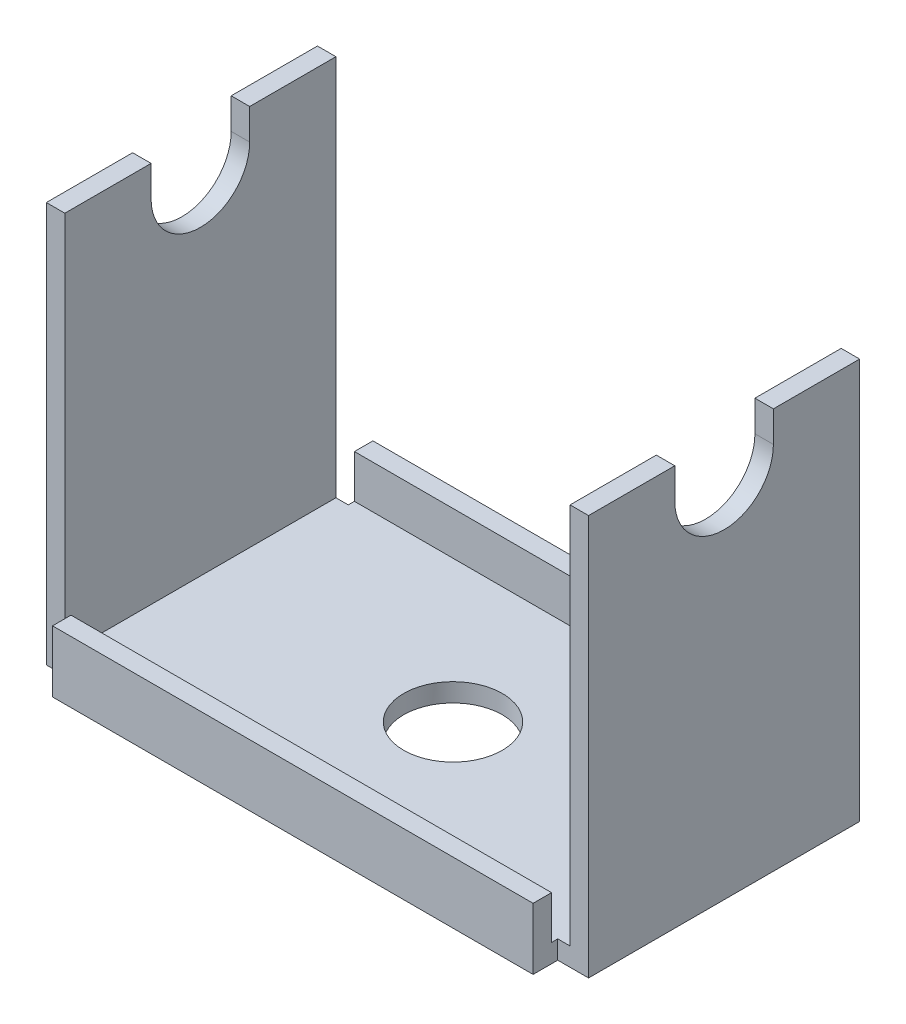
SolidWorks part; units mm, degrees
ref_plane "Front Plane" through (0, 0, 0) normal (0, 0, 1) x (1, 0, 0)
ref_plane "Top Plane" through (0, 0, 0) normal (0, 1, 0) x (1, 0, 0)
ref_plane "Right Plane" through (0, 0, 0) normal (1, 0, 0) x (0, 0, -1)
sketch "Sketch1" plane through (0, 0, 0) normal (0, 0, 1) x (1, 0, 0)
  line L0 (-22, 32.5) -> (-22, 0)
  line L1 (-22, 0) -> (22, 0)
  line L2 (22, 0) -> (22, 32.5)
  line L3 (22, 32.5) -> (20.5, 32.5)
  line L4 (20.5, 32.5) -> (20.5, 1.5)
  line L5 (20.5, 1.5) -> (-20.5, 1.5)
  line L6 (-20.5, 1.5) -> (-20.5, 32.5)
  line L7 (-20.5, 32.5) -> (-22, 32.5)
  dimension "D1" = 1.5
  dimension "D2" = 1.5
  dimension "D3" = 32.5
  dimension "D4" = 44
extrude "Boss-Extrude1" add sketch "Sketch1" against normal mid plane 22
sketch "Sketch2" plane through (0, 0, 0) normal (1, 0, 0) x (0, 0, -1)
  line L0 (-11, 0) -> (-13, 0)
  line L1 (-13, 0) -> (-13, 5)
  line L2 (-13, 5) -> (-11.5, 5)
  line L3 (-11.5, 5) -> (-11.5, 1.5)
  line L4 (-11.5, 1.5) -> (-11, 1.5)
  line L5 (-11, 0) -> (-11, 32.5) construction
  line L6 (-11, 1.5) -> (-11, 0)
  dimension "D1" = 1.5
  dimension "D2" = 0.5
  dimension "D3" = 5
extrude "Boss-Extrude2" add sketch "Sketch2" along normal mid plane 39
mirror "Mirror1" about plane through (0, 0, 0) normal (0, 0, 1) of "Boss-Extrude2"
sketch "Sketch3" plane through (0, 1.5, 0) normal (0, 1, 0) x (-1, 0, 0)
  line L0 (0, 0) -> (0, -11.5) construction
  line L1 (-19.5, -11.5) -> (19.5, -11.5) construction
  line L2 (0, 0) -> (-20.5, 0) construction
  line L3 (-20.5, -11) -> (-20.5, 11) construction
  circle A0 centre (0, 0) radius 4
  dimension "D1" = 8
extrude "Cut-Extrude1" cut sketch "Sketch3" against normal through all
sketch "Sketch4" plane through (22, 0, 0) normal (1, 0, 0) x (0, 0, -1)
  line L0 (0, 30) -> (0, 32.5) construction
  line L1 (11, 32.5) -> (-11, 32.5) construction
  line L2 (11, 0) -> (-11, 0) construction
  line L3 (-4, 30) -> (-4, 32.5)
  line L4 (-4, 32.5) -> (4, 32.5)
  line L5 (4, 32.5) -> (4, 30)
  arc A0 (-4, 30) -> (4, 30) centre (0, 30) ccw
  dimension "D2" = 4
  dimension "D1" = 30
extrude "Cut-Extrude2" cut sketch "Sketch4" against normal through all
